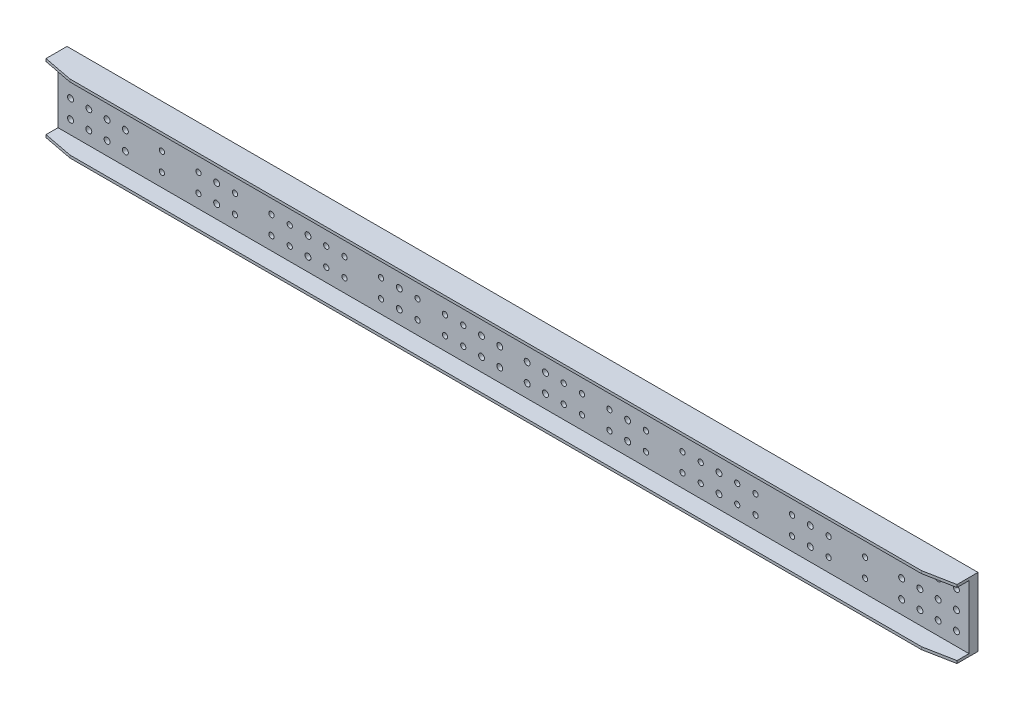
SolidWorks part; units mm, degrees
ref_plane "前视" through (0, 0, 0) normal (0, 0, 1) x (1, 0, 0)
ref_plane "上视" through (0, 0, 0) normal (0, 1, 0) x (1, 0, 0)
ref_plane "右视" through (0, 0, 0) normal (1, 0, 0) x (0, 0, -1)
sketch "草图1" plane through (0, 0, 0) normal (0, 0, 1) x (1, 0, 0)
  line L0 (0, 280.187) -> (0, -298.191) construction
  line L1 (-2057.2074, 0) -> (2116.7847, 0) construction
  line L2 (2116.7847, 80) -> (-2430.1435, 80) construction
  line L3 (-1995, 150) -> (1995, 150)
  line L5 (-1995, -150) -> (1995, -150)
  line L6 (1995, 150) -> (1995, -150)
  line L7 (-2430.1435, -80) -> (2116.7847, -80) construction
  line L8 (1940, 266.4652) -> (1940, -249.2739) construction
  line L9 (1860, -249.2739) -> (1860, 266.4652) construction
  line L10 (1060, 266.4652) -> (1060, -361.7988) construction
  line L11 (1780, 266.4652) -> (1780, -249.2739) construction
  line L12 (1780, -249.2739) -> (1700, -249.2739) construction
  line L13 (1700, -249.2739) -> (1700, 266.4652) construction
  line L14 (1540, 266.4652) -> (1540, -361.7988) construction
  line L15 (1380, 266.4652) -> (1380, -361.7988) construction
  line L16 (1220, -361.7988) -> (1220, 266.4652) construction
  line L17 (980, -361.7988) -> (980, 266.4652) construction
  line L18 (740, -361.7988) -> (740, 464.33) construction
  line L19 (820, 266.4652) -> (820, -361.7988) construction
  line L20 (580, -361.7988) -> (580, 266.4652) construction
  line L21 (420, -361.7988) -> (420, 266.4652) construction
  line L22 (300, -298.191) -> (300, 266.4652) construction
  line L23 (60, 280.187) -> (60, -298.191) construction
  line L24 (140, 280.187) -> (140, -298.191) construction
  line L25 (220, -298.191) -> (220, 280.187) construction
  line L26 (-1995, 150) -> (-1995, -150)
  circle A0 centre (1940, 80) radius 13
  circle A1 centre (1860, 80) radius 13
  circle A2 centre (1780, 80) radius 13
  circle A3 centre (1700, 80) radius 13
  circle A4 centre (1540, 80) radius 11.5
  circle A5 centre (1380, 80) radius 11.5
  circle A6 centre (1220, 80) radius 11.5
  circle A7 centre (1060, 80) radius 11.5
  circle A8 centre (980, 80) radius 11.5
  circle A9 centre (820, 80) radius 11.5
  circle A10 centre (740, 80) radius 11.5
  circle A11 centre (580, 80) radius 11.5
  circle A12 centre (980, 0) radius 11.5
  circle A13 centre (1060, 0) radius 11.5
  circle A14 centre (820, 0) radius 11.5
  circle A15 centre (740, 0) radius 11.5
  circle A16 centre (580, 0) radius 11.5
  circle A17 centre (1220, 0) radius 11.5
  circle A18 centre (1380, 0) radius 11.5
  circle A19 centre (1540, 0) radius 11.5
  circle A20 centre (1700, 0) radius 13
  circle A21 centre (1780, 0) radius 13
  circle A22 centre (1860, 0) radius 13
  circle A23 centre (1940, 0) radius 13
  circle A24 centre (420, 80) radius 11.5
  circle A25 centre (420, 0) radius 11.5
  circle A26 centre (300, 0) radius 11.5
  circle A27 centre (300, 80) radius 11.5
  circle A28 centre (220, 80) radius 11.5
  circle A29 centre (220, 0) radius 11.5
  circle A30 centre (140, 0) radius 13
  circle A31 centre (140, 80) radius 13
  circle A32 centre (60, 80) radius 13
  circle A33 centre (60, 0) radius 13
  circle A34 centre (1700, -80) radius 13
  circle A35 centre (1780, -80) radius 13
  circle A36 centre (1860, -80) radius 13
  circle A37 centre (1940, -80) radius 13
  circle A38 centre (580, -80) radius 11.5
  circle A39 centre (740, -80) radius 11.5
  circle A40 centre (820, -80) radius 11.5
  circle A41 centre (980, -80) radius 11.5
  circle A42 centre (1060, -80) radius 11.5
  circle A43 centre (1220, -80) radius 11.5
  circle A44 centre (1380, -80) radius 11.5
  circle A45 centre (1540, -80) radius 11.5
  circle A46 centre (220, -80) radius 11.5
  circle A47 centre (300, -80) radius 11.5
  circle A48 centre (420, -80) radius 11.5
  circle A49 centre (580, -80) radius 11.5
  circle A50 centre (60, -80) radius 13
  circle A51 centre (140, -80) radius 13
  circle A52 centre (-140, -80) radius 13
  circle A53 centre (-60, -80) radius 13
  circle A54 centre (-580, -80) radius 11.5
  circle A55 centre (-420, -80) radius 11.5
  circle A56 centre (-300, -80) radius 11.5
  circle A57 centre (-220, -80) radius 11.5
  circle A58 centre (-1540, -80) radius 11.5
  circle A59 centre (-1380, -80) radius 11.5
  circle A60 centre (-1220, -80) radius 11.5
  circle A61 centre (-1060, -80) radius 11.5
  circle A62 centre (-980, -80) radius 11.5
  circle A63 centre (-820, -80) radius 11.5
  circle A64 centre (-740, -80) radius 11.5
  circle A65 centre (-580, -80) radius 11.5
  circle A66 centre (-1940, -80) radius 13
  circle A67 centre (-1860, -80) radius 13
  circle A68 centre (-1780, -80) radius 13
  circle A69 centre (-1700, -80) radius 13
  circle A70 centre (-60, 0) radius 13
  circle A71 centre (-60, 80) radius 13
  circle A72 centre (-140, 80) radius 13
  circle A73 centre (-140, 0) radius 13
  circle A74 centre (-220, 0) radius 11.5
  circle A75 centre (-220, 80) radius 11.5
  circle A76 centre (-300, 80) radius 11.5
  circle A77 centre (-300, 0) radius 11.5
  circle A78 centre (-420, 0) radius 11.5
  circle A79 centre (-420, 80) radius 11.5
  circle A80 centre (-1940, 0) radius 13
  circle A81 centre (-1860, 0) radius 13
  circle A82 centre (-1780, 0) radius 13
  circle A83 centre (-1700, 0) radius 13
  circle A84 centre (-1540, 0) radius 11.5
  circle A85 centre (-1380, 0) radius 11.5
  circle A86 centre (-1220, 0) radius 11.5
  circle A87 centre (-580, 0) radius 11.5
  circle A88 centre (-740, 0) radius 11.5
  circle A89 centre (-820, 0) radius 11.5
  circle A90 centre (-1060, 0) radius 11.5
  circle A91 centre (-980, 0) radius 11.5
  circle A92 centre (-580, 80) radius 11.5
  circle A93 centre (-740, 80) radius 11.5
  circle A94 centre (-820, 80) radius 11.5
  circle A95 centre (-980, 80) radius 11.5
  circle A96 centre (-1060, 80) radius 11.5
  circle A97 centre (-1220, 80) radius 11.5
  circle A98 centre (-1380, 80) radius 11.5
  circle A99 centre (-1540, 80) radius 11.5
  circle A100 centre (-1700, 80) radius 13
  circle A101 centre (-1780, 80) radius 13
  circle A102 centre (-1860, 80) radius 13
  circle A103 centre (-1940, 80) radius 13
  dimension "D22" = 23
  dimension "D23" = 26
  dimension "D24" = 26
  dimension "D1" = 3990
  dimension "D2" = 300
  dimension "D3" = 70
  dimension "D4" = 80
  dimension "D5" = 55
  dimension "D6" = 80
  dimension "D7" = 80
  dimension "D8" = 80
  dimension "D9" = 455
  dimension "D10" = 160
  dimension "D11" = 160
  dimension "D12" = 160
  dimension "D13" = 80
  dimension "D14" = 160
  dimension "D15" = 80
  dimension "D16" = 160
  dimension "D17" = 160
  dimension "D18" = 120
  dimension "D19" = 60
  dimension "D20" = 80
  dimension "D21" = 80
extrude "基体-拉伸" add sketch "草图1" along normal blind 39.5
sketch "草图2" plane through (0, 0, 39.5) normal (0, 0, 1) x (1, 0, 0)
  line L0 (1995, -150) -> (1995, 150) construction
  line L1 (-1995, 150) -> (1995, 150)
  line L2 (-1995, 150) -> (-1995, 138.5)
  line L3 (-1995, 138.5) -> (1995, 138.5)
  line L4 (1995, 150) -> (1995, 138.5)
  line L5 (0, 0) -> (2507.3409, 0) construction
  line L6 (1995, -150) -> (1995, -138.5)
  line L7 (-1995, -138.5) -> (1995, -138.5)
  line L8 (-1995, -150) -> (-1995, -138.5)
  line L9 (-1995, -150) -> (1995, -150)
  dimension "D1" = 11.5
extrude "凸台-拉伸1" add sketch "草图2" along normal blind 77.5
sketch "草图3" plane through (0, 0, 0) normal (0, 0, -1) x (-1, 0, 0)
  line L0 (0, 0) -> (2381.8358, 0) construction
  line L1 (0, 348.8193) -> (0, -302.4645) construction
  line L2 (1300, 348.8193) -> (1300, -385.903) construction
  line L3 (1995, 150) -> (1995, -150) construction
  line L4 (900, 237.7997) -> (900, -385.903) construction
  line L5 (1265, 115) -> (1335, 115)
  line L6 (1265, 115) -> (1265, -115)
  line L7 (1265, -115) -> (1335, -115)
  line L8 (1335, 115) -> (1335, -115)
  line L9 (865, 115) -> (935, 115)
  line L10 (865, 115) -> (865, -115)
  line L11 (865, -115) -> (935, -115)
  line L12 (935, 115) -> (935, -115)
  line L13 (500, -385.903) -> (500, 237.7997) construction
  line L14 (-1265, 115) -> (-1335, 115)
  line L15 (535, -115) -> (465, -115)
  line L16 (535, -115) -> (535, 115)
  line L17 (535, 115) -> (465, 115)
  line L18 (465, -115) -> (465, 115)
  line L19 (-1335, 115) -> (-1335, -115)
  line L20 (-1265, 115) -> (-1265, -115)
  line L21 (-1265, -115) -> (-1335, -115)
  line L22 (-865, -115) -> (-935, -115)
  line L23 (-935, 115) -> (-935, -115)
  line L24 (-865, 115) -> (-935, 115)
  line L25 (-865, 115) -> (-865, -115)
  line L26 (-535, -115) -> (-535, 115)
  line L27 (-535, -115) -> (-465, -115)
  line L28 (-465, -115) -> (-465, 115)
  line L29 (-535, 115) -> (-465, 115)
  dimension "D1" = 695
  dimension "D2" = 70
  dimension "D3" = 230
  dimension "D4" = 400
  dimension "D5" = 70
  dimension "D6" = 230
  dimension "D7" = 400
  dimension "D8" = 70
  dimension "D9" = 230
extrude "凸台-拉伸2" add sketch "草图3" along normal blind 16
sketch "草图4" plane through (0, 0, 39.5) normal (0, 0, 1) x (1, 0, 0)
  line L0 (0, 0) -> (2249.2348, 0) construction
  line L1 (0, 0) -> (0, 1256.1111) construction
  line L2 (1300, 296.2067) -> (1300, -332.3633) construction
  line L3 (900, -332.3633) -> (900, 296.2067) construction
  line L4 (1995, -138.5) -> (1995, 138.5) construction
  line L5 (500, 260.05) -> (500, -332.3633) construction
  line L6 (1458.5104, 80) -> (376.6321, 80) construction
  circle A0 centre (1300, 80) radius 13
  circle A1 centre (900, 80) radius 13
  circle A2 centre (900, 0) radius 13
  circle A3 centre (1300, 0) radius 13
  circle A4 centre (900, -80) radius 13
  circle A5 centre (1300, -80) radius 13
  circle A6 centre (500, 80) radius 13
  circle A7 centre (500, 0) radius 13
  circle A8 centre (500, -80) radius 13
  circle A9 centre (-500, -80) radius 13
  circle A10 centre (-500, 0) radius 13
  circle A11 centre (-500, 80) radius 13
  circle A12 centre (-1300, -80) radius 13
  circle A13 centre (-900, -80) radius 13
  circle A14 centre (-1300, 0) radius 13
  circle A15 centre (-900, 0) radius 13
  circle A16 centre (-900, 80) radius 13
  circle A17 centre (-1300, 80) radius 13
  dimension "D5" = 26
  dimension "D1" = 695
  dimension "D2" = 400
  dimension "D3" = 400
  dimension "D4" = 80
extrude "切除-拉伸1" cut sketch "草图4" against normal through all
sketch "草图5" plane through (0, 150, 0) normal (0, 1, 0) x (-1, 0, 0)
  line L0 (-1995, 92) -> (-1995, 117)
  line L1 (-1995, 117) -> (-1995, 0) construction
  line L2 (-1995, 117) -> (-1865, 117)
  line L3 (-1995, 117) -> (1995, 117) construction
  line L4 (-1865, 117) -> (-1995, 92)
  line L5 (0, 174.8481) -> (0, -119.4889) construction
  line L6 (1865, 117) -> (1995, 92)
  line L7 (1995, 117) -> (1865, 117)
  line L8 (1995, 92) -> (1995, 117)
  dimension "D1" = 130
  dimension "D2" = 25
extrude "切除-拉伸2" cut sketch "草图5" against normal through all
